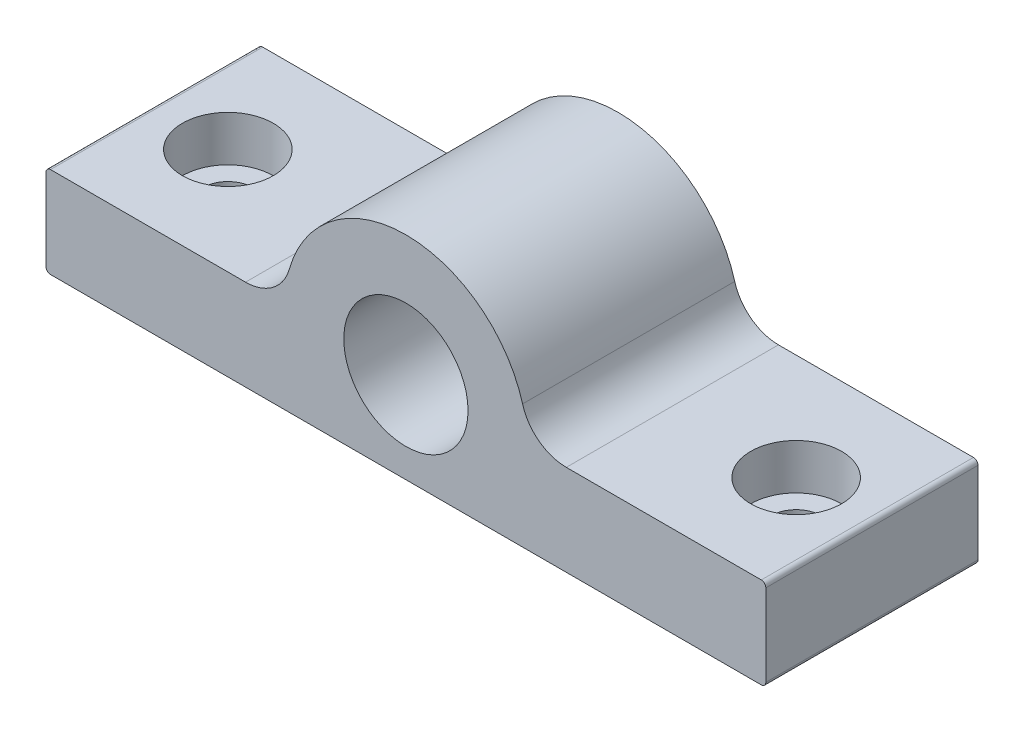
SolidWorks part; units mm, degrees
ref_plane "Front Plane" through (0, 0, 0) normal (0, 0, 1) x (1, 0, 0)
ref_plane "Top Plane" through (0, 0, 0) normal (0, 1, 0) x (1, 0, 0)
ref_plane "Right Plane" through (0, 0, 0) normal (1, 0, 0) x (0, 0, -1)
sketch "Sketch1" plane through (0, 0, 0) normal (0, 1, 0) x (1, 0, 0)
  line L1 (0, 0) -> (47.5, 0)
  line L2 (0, 0) -> (0, 14)
  line L3 (0, 14) -> (47.5, 14)
  line L4 (47.5, 0) -> (47.5, 14)
  dimension "D1" = 14
  dimension "D2" = 47.5
extrude "Boss-Extrude1" add sketch "Sketch1" along normal blind 6
sketch "Sketch3" plane through (0, 0, 0) normal (0, 0, 1) x (1, 0, 0)
  line L0 (0, 0) -> (47.5, 0) construction
  line L1 (16.7187, 2.1841) -> (30.7813, 2.1841)
  line L2 (15.75, 6) -> (15.75, 2.1841)
  line L3 (31.75, 6) -> (31.75, 2.1841)
  line L4 (15.75, 2.1841) -> (31.75, 2.1841)
  arc A0 (31.75, 6) -> (15.75, 6) centre (23.75, 6) ccw
  line M5 (47.5, 6) -> (0, 6)
  dimension "D1" = 16
  dimension "D2" = 6
extrude "Boss-Extrude2" add sketch "Sketch3" against normal up to surface (14 mm away) contours A0 M5 up to face at (23.75, 3, -14)
sketch "Sketch4" plane through (0, 0, 0) normal (0, 0, 1) x (1, 0, 0)
  circle A0 centre (23.75, 6) radius 4.1
  dimension "D1" = 8.2
extrude "Cut-Extrude1" cut sketch "Sketch4" against normal through all
sketch "Sketch5" plane through (0, 6, 0) normal (0, 1, 0) x (1, 0, 0)
  line L0 (0, 7) -> (47.5, 7) construction
  line L1 (0, 14) -> (0, 0) construction
  line L2 (47.5, 0) -> (47.5, 14) construction
  line L3 (23.75, 5.6405) -> (23.75, 9.1031) construction
  circle A0 centre (5, 7) radius 1.65
  circle A1 centre (42.5, 7) radius 1.65
  dimension "D1" = 3.3
  dimension "D2" = 5
extrude "Cut-Extrude2" cut sketch "Sketch5" against normal through all
sketch "Sketch6" plane through (0, 6, 0) normal (0, 1, 0) x (1, 0, 0)
  line L0 (0, 7) -> (47.5, 7) construction
  line L1 (0, 14) -> (0, 0) construction
  line L2 (47.5, 0) -> (47.5, 14) construction
  line L3 (23.75, 6.5412) -> (23.75, 7.7129) construction
  circle A0 centre (5, 7) radius 3
  circle A1 centre (42.5, 7) radius 3
  dimension "D1" = 6
extrude "Cut-Extrude3" cut sketch "Sketch6" against normal blind 3
fillet "Fillet1" radius 3 2 edges at (15.75, 6, -7) (31.75, 6, -7)
fillet "Fillet2" radius 0.3 4 edges at (0, 0, -7) (0, 6, -7) (47.5, 0, -7) (47.5, 6, -7)
